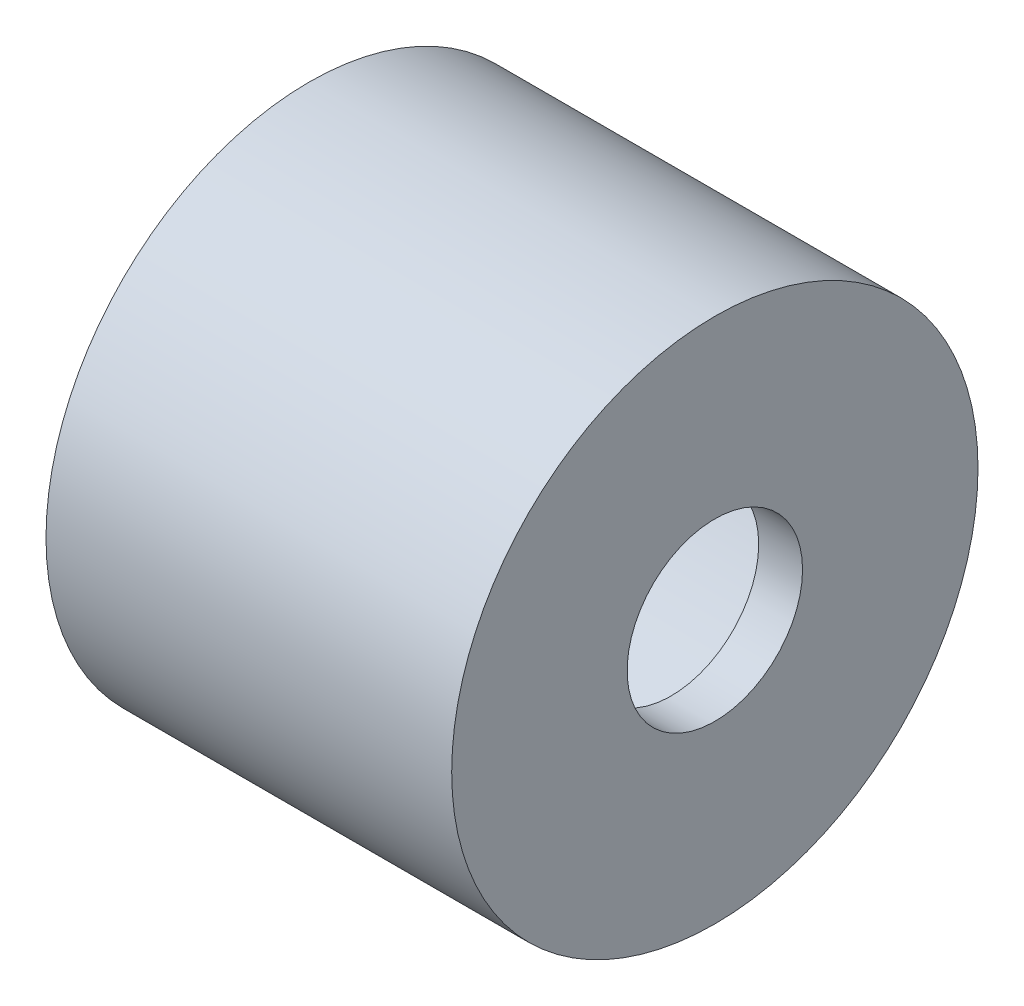
SolidWorks part; units mm, degrees
ref_plane "Front Plane" through (0, 0, 0) normal (0, 0, 1) x (1, 0, 0)
ref_plane "Top Plane" through (0, 0, 0) normal (0, 1, 0) x (1, 0, 0)
ref_plane "Right Plane" through (0, 0, 0) normal (1, 0, 0) x (0, 0, -1)
sketch "Sketch2" plane through (0, 0, 0) normal (1, 0, 0) x (0, 0, -1)
  circle A0 centre (0, 0) radius 152.4
  circle A1 centre (0, 0) radius 50.8
  point P2 (0, 0)
  dimension "D1" = 304.8
  dimension "D2" = 101.6
extrude "Boss-Extrude1" add sketch "Sketch2" along normal blind 25.4 from offset 76.2
sketch "Sketch3" plane through (76.2, 0, 0) normal (-1, 0, 0) x (0, 0, 1)
  circle A0 centre (0, 0) radius 152.4 construction
  circle A1 centre (0, 0) radius 152.4
  circle A2 centre (0, 0) radius 139.7
  circle M3 centre (0, 0) radius 152.4
  dimension "D1" = 12.7
extrude "Boss-Extrude2" add sketch "Sketch3" along normal blind 203.2 contours A2 M3 | A1
sketch "Sketch4" plane through (-127, 0, 0) normal (-1, 0, 0) x (0, 0, 1)
  circle A0 centre (0, 0) radius 152.4 construction
  circle A1 centre (0, 0) radius 139.7 construction
  circle A2 centre (0, 0) radius 152.4
  circle A3 centre (0, 0) radius 139.7
ref_plane "Plane1" through (-254, 0, 0) normal (-1, 0, 0) x (0, 0, 1)
sketch "Sketch5" plane through (-254, 0, 0) normal (-1, 0, 0) x (0, 0, 1)
  line L0 (0, 0) -> (-6.35, 0) construction
  line L1 (0, 76.2) -> (0, -76.2) construction
  line L2 (-6.35, 88.9) -> (-6.35, -88.9) construction
  line L3 (-6.35, 88.9) -> (-6.35, -88.9) construction
  line L4 (19.05, 88.9) -> (19.05, -88.9)
  line L5 (-31.75, 88.9) -> (-31.75, -88.9)
  line L6 (-6.35, 88.9) -> (-6.35, -88.9) construction
  line L7 (31.75, 88.9) -> (31.75, -88.9)
  line L8 (-44.45, 88.9) -> (-44.45, -88.9)
  arc A0 (19.05, 88.9) -> (-31.75, 88.9) centre (-6.35, 88.9) ccw
  arc A1 (-31.75, -88.9) -> (19.05, -88.9) centre (-6.35, -88.9) ccw
  arc A2 (31.75, 88.9) -> (-44.45, 88.9) centre (-6.35, 88.9) ccw
  arc A3 (-44.45, -88.9) -> (31.75, -88.9) centre (-6.35, -88.9) ccw
  point P4 (-6.35, 0)
  point P7 (-6.35, 0)
  point P14 (-6.35, 0)
  dimension "D3" = 25.4
  dimension "D4" = 38.1
  dimension "D1" = 177.8
  dimension "D2" = 6.35
extrude "Boss-Extrude3" add sketch "Sketch4" along normal blind 6.35 contours A2
extrude "Cut-Extrude1" cut sketch "Sketch5" against normal blind 6.35 from surface at -120.65 contours L5 A1 L4 A0 | A2 L8 A3 L7
